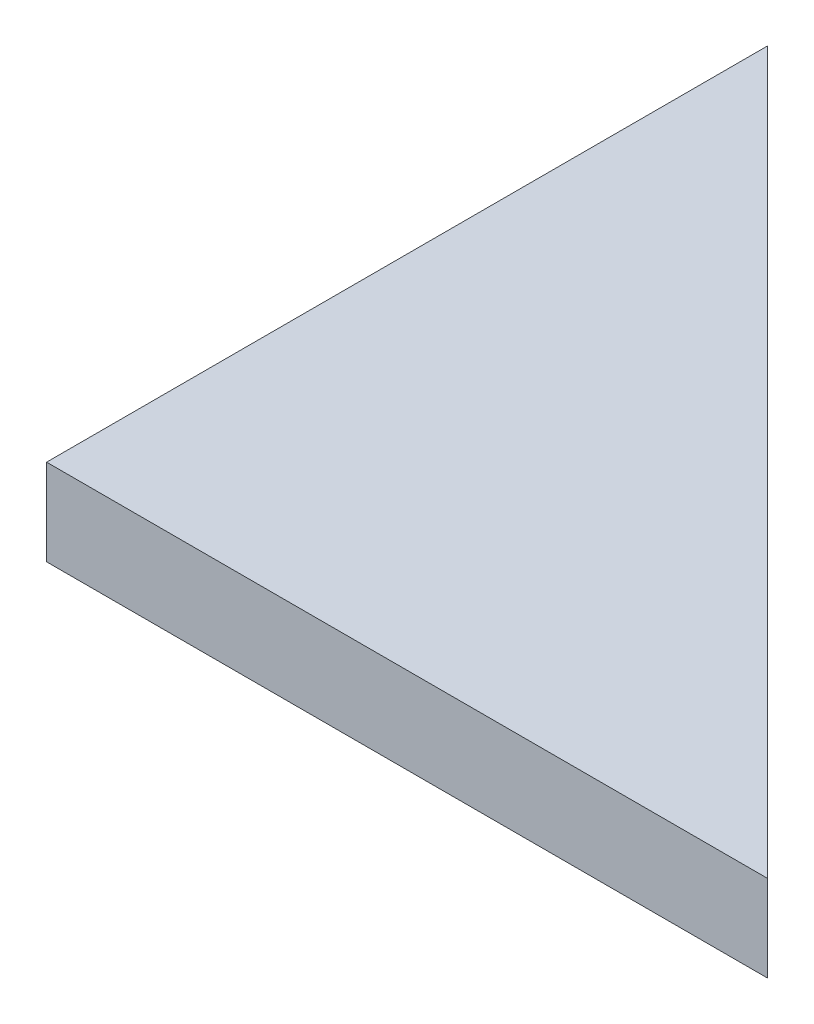
SolidWorks part; units mm, degrees
material "Plywood"
ref_plane "Front Plane" through (0, 0, 0) normal (0, 0, 1) x (1, 0, 0)
ref_plane "Top Plane" through (0, 0, 0) normal (0, 1, 0) x (1, 0, 0)
ref_plane "Right Plane" through (0, 0, 0) normal (1, 0, 0) x (0, 0, -1)
sketch "Sketch1" plane through (0, 0, 0) normal (0, 1, 0) x (1, 0, 0)
  line L0 (0, 0) -> (0, 152.4)
  line L1 (0, 0) -> (152.4, 0)
  line L2 (0, 152.4) -> (152.4, 0)
  dimension "D1" = 152.4
extrude "Boss-Extrude1" add sketch "Sketch1" along normal blind 18.2562
